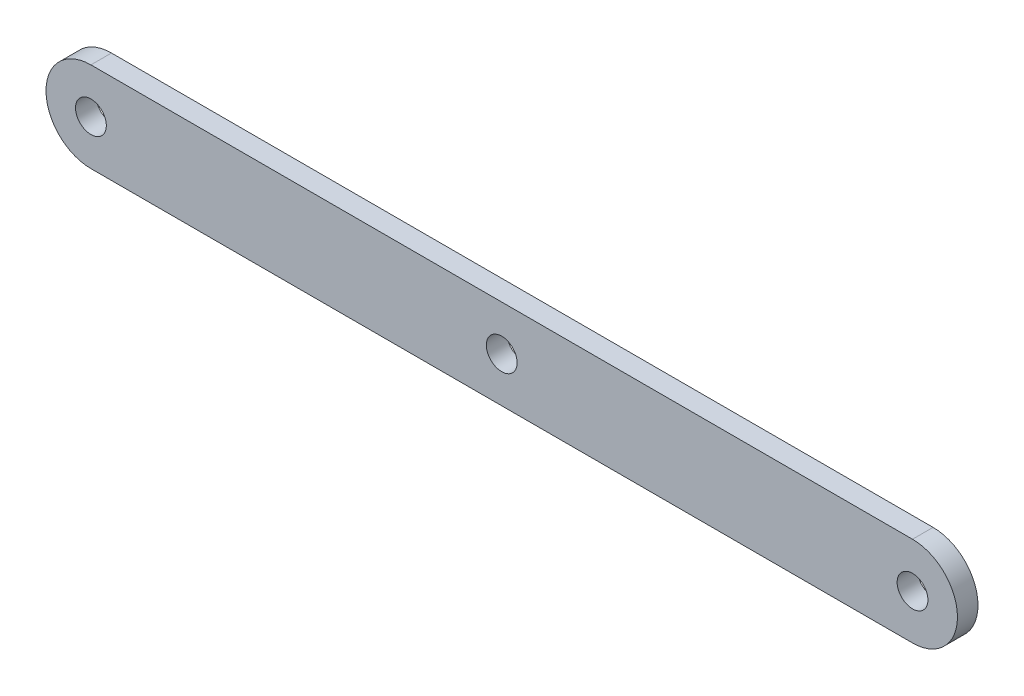
SolidWorks part; units mm, degrees
ref_plane "Front Plane" through (0, 0, 0) normal (0, 0, 1) x (1, 0, 0)
ref_plane "Top Plane" through (0, 0, 0) normal (0, 1, 0) x (1, 0, 0)
ref_plane "Right Plane" through (0, 0, 0) normal (1, 0, 0) x (0, 0, -1)
sketch "Sketch1" plane through (0, 0, 0) normal (0, 0, 1) x (1, 0, 0)
  line L0 (656.4105, 77.2177) -> (656.4105, -97.7823) construction
  line L1 (-93.5895, 77.2177) -> (1406.4105, 77.2177)
  line L3 (-93.5895, -97.7823) -> (1406.4105, -97.7823)
  arc A0 (-93.5895, 77.2177) -> (-93.5895, -97.7823) centre (-93.5895, -10.2823) ccw
  arc A1 (1406.4105, -97.7823) -> (1406.4105, 77.2177) centre (1406.4105, -10.2823) ccw
  circle A2 centre (-93.5895, -10.2823) radius 30
  circle A3 centre (1406.4105, -10.2823) radius 30
  circle A4 centre (656.4105, -10.2823) radius 30
sketch "Sketch2" plane through (0, 0, 0) normal (0, 0, 1) x (1, 0, 0)
  line L0 (656.4105, 77.2177) -> (656.4105, -97.7823) construction
  line L1 (-93.5895, 77.2177) -> (1506.4105, 77.2177)
  line L2 (-93.5895, -97.7823) -> (1506.4105, -97.7823)
  arc A0 (-93.5895, 77.2177) -> (-93.5895, -97.7823) centre (-93.5895, -10.2823) ccw
  arc A1 (1506.4105, -97.7823) -> (1506.4105, 77.2177) centre (1506.4105, -10.2823) ccw
  circle A2 centre (-93.5895, -10.2823) radius 30
  circle A3 centre (1506.4105, -10.2823) radius 30
  circle A4 centre (706.4105, -10.2823) radius 30
  dimension "D1" = 800
extrude "Boss-Extrude1" add sketch "Sketch2" along normal blind 40
